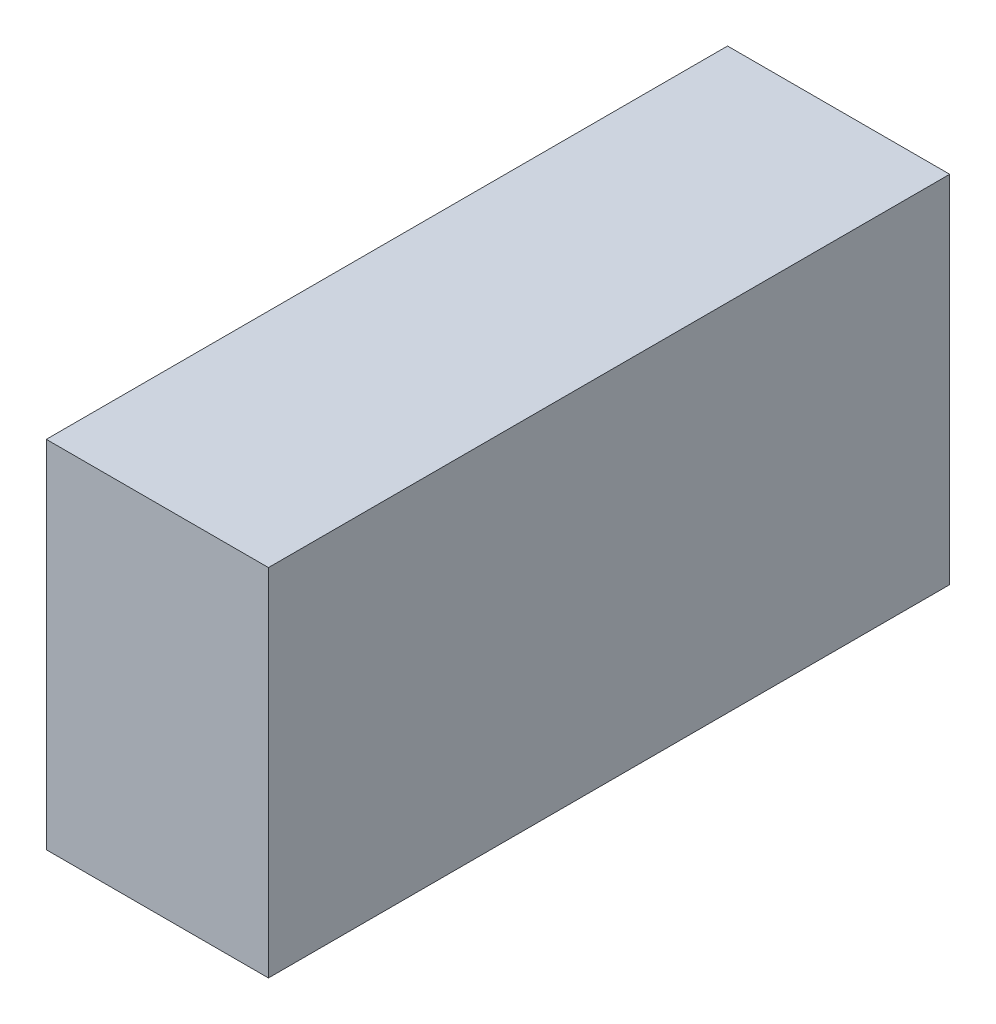
SolidWorks part; units mm, degrees
ref_plane "Front Plane" through (0, 0, 0) normal (0, 0, 1) x (1, 0, 0)
ref_plane "Top Plane" through (0, 0, 0) normal (0, 1, 0) x (1, 0, 0)
ref_plane "Right Plane" through (0, 0, 0) normal (1, 0, 0) x (0, 0, -1)
sketch "Sketch2" plane through (0, 0, 0) normal (0, 1, 0) x (1, 0, 0)
  line L0 (22.5, 0) -> (-22.5, 0) construction
  line L1 (-22.5, -69) -> (22.5, -69)
  line L2 (-22.5, -69) -> (-22.5, 69)
  line L3 (-22.5, 69) -> (22.5, 69)
  line L4 (22.5, -69) -> (22.5, 69)
  point P4 (22.5, 0)
  point P8 (0, 69)
  dimension "D1" = 138
  dimension "D2" = 45
extrude "6500mah battery" add sketch "Sketch2" along normal blind 72
sketch "Sketch3" plane through (22.5, 0, 0) normal (1, 0, 0) x (0, 0, -1)
  line L0 (0, 72) -> (0, 0) construction
  line L1 (-69, 72) -> (69, 72) construction
